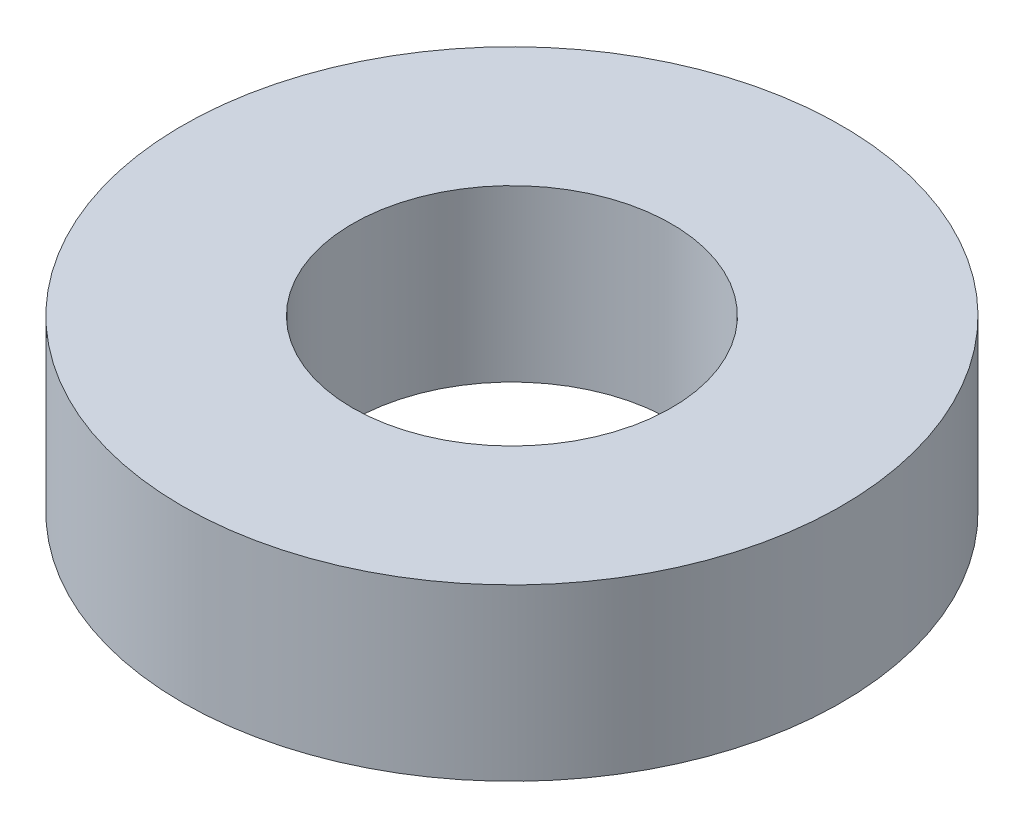
SolidWorks part; units mm, degrees
ref_plane "Front Plane" through (0, 0, 0) normal (0, 0, 1) x (1, 0, 0)
ref_plane "Top Plane" through (0, 0, 0) normal (0, 1, 0) x (1, 0, 0)
ref_plane "Right Plane" through (0, 0, 0) normal (1, 0, 0) x (0, 0, -1)
sketch "Sketch1" plane through (0, 0, 0) normal (0, 1, 0) x (1, 0, 0)
  circle A0 centre (0, 0) radius 31
  circle A1 centre (0, 0) radius 15
  dimension "D1" = 62
  dimension "D2" = 30
extrude "Boss-Extrude1" add sketch "Sketch1" along normal blind 16
